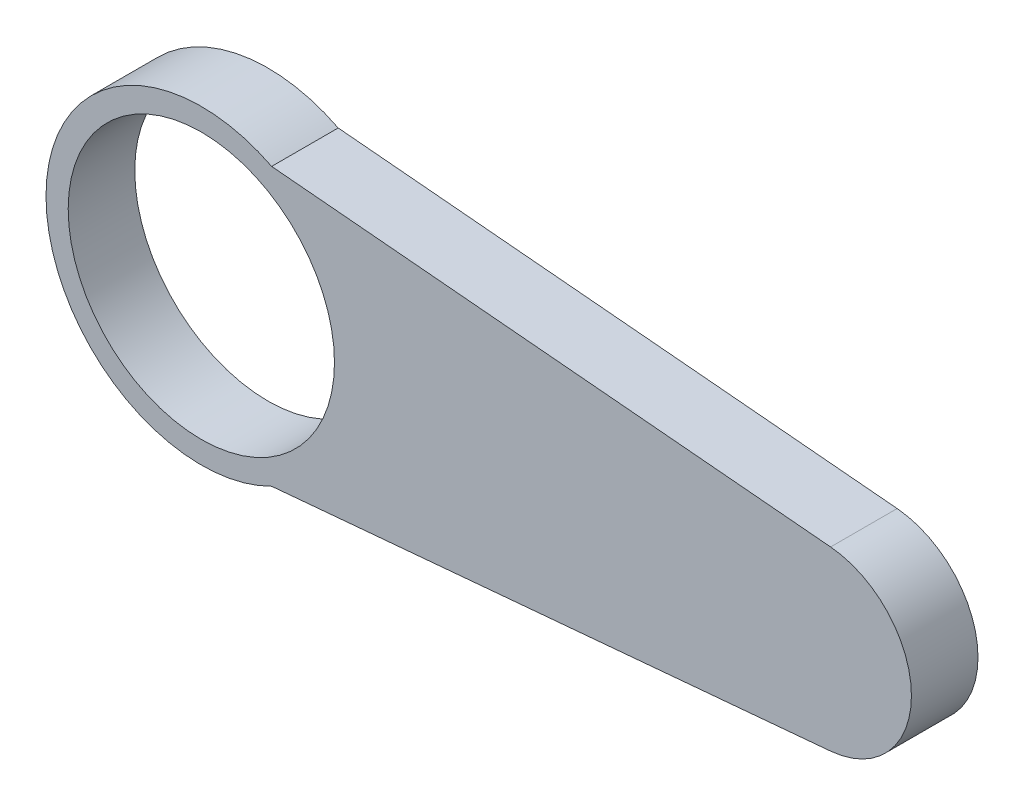
SolidWorks part; units mm, degrees
ref_plane "Front Plane" through (0, 0, 0) normal (0, 0, 1) x (1, 0, 0)
ref_plane "Top Plane" through (0, 0, 0) normal (0, 1, 0) x (1, 0, 0)
ref_plane "Right Plane" through (0, 0, 0) normal (1, 0, 0) x (0, 0, -1)
sketch "Sketch1" plane through (0, 0, 0) normal (0, 0, 1) x (1, 0, 0)
  line L0 (1.584, 3.121) -> (14.1786, 1.992)
  line L1 (-3.5, 0) -> (16, 0) construction
  line L2 (14.1786, -1.992) -> (1.584, -3.121)
  arc A0 (1.584, 3.121) -> (1.584, -3.121) centre (0, 0) ccw
  circle A1 centre (0, 0) radius 3
  arc A2 (0.2902, 3.237) -> (0.2902, -3.237) centre (0, 0) ccw construction
  arc A3 (14.1786, -1.992) -> (14.1786, 1.992) centre (14, 0) ccw
  point P4 (2.382, -2.205)
  point P10 (0.2902, 3.121)
  point P11 (0, 0)
  dimension "D2" = 6
  dimension "D3" = 3.25
  dimension "D4" = 3.5
  dimension "D5" = 2
  dimension "D1" = 19.5
extrude "Boss-Extrude1" add sketch "Sketch1" along normal blind 1.5
